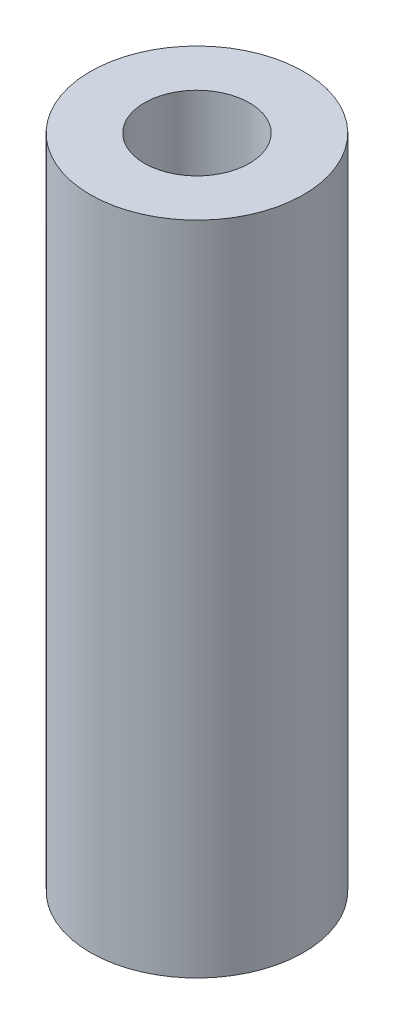
SolidWorks part; units mm, degrees
ref_plane "Front Plane" through (0, 0, 0) normal (0, 0, 1) x (1, 0, 0)
ref_plane "Top Plane" through (0, 0, 0) normal (0, 1, 0) x (1, 0, 0)
ref_plane "Right Plane" through (0, 0, 0) normal (1, 0, 0) x (0, 0, -1)
sketch "Sketch1" plane through (0, 0, 0) normal (0, 1, 0) x (1, 0, 0)
  circle A0 centre (0, 0) radius 3.25
  circle A1 centre (0, 0) radius 1.6
  dimension "D1" = 3.2
  dimension "D2" = 6.5
extrude "Boss-Extrude1" add sketch "Sketch1" along normal blind 20
